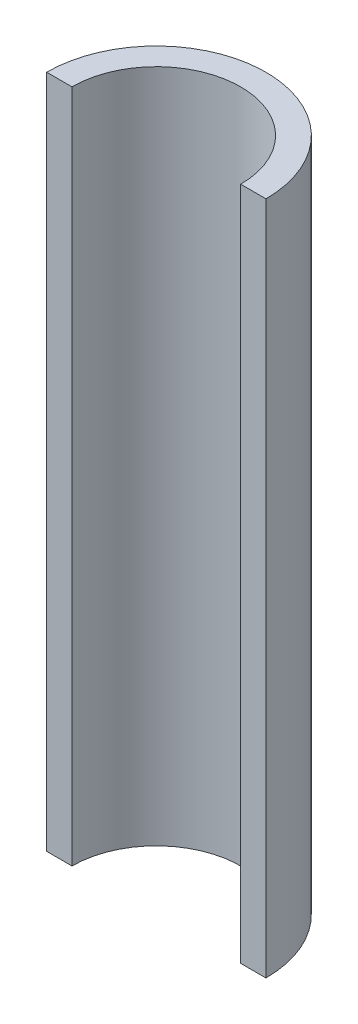
SolidWorks part; units mm, degrees
ref_plane "Front Plane" through (0, 0, 0) normal (0, 0, 1) x (1, 0, 0)
ref_plane "Top Plane" through (0, 0, 0) normal (0, 1, 0) x (1, 0, 0)
ref_plane "Right Plane" through (0, 0, 0) normal (1, 0, 0) x (0, 0, -1)
sketch "Sketch1" plane through (0, 0, 0) normal (0, 1, 0) x (1, 0, 0)
  line L0 (-13, 0) -> (-10, 0)
  line L1 (10, 0) -> (13, 0)
  arc A0 (10, 0) -> (-10, 0) centre (0, 0) ccw
  arc A1 (13, 0) -> (-13, 0) centre (0, 0) ccw
  dimension "D1" = 20
  dimension "D2" = 3
extrude "Boss-Extrude1" add sketch "Sketch1" along normal blind 80
